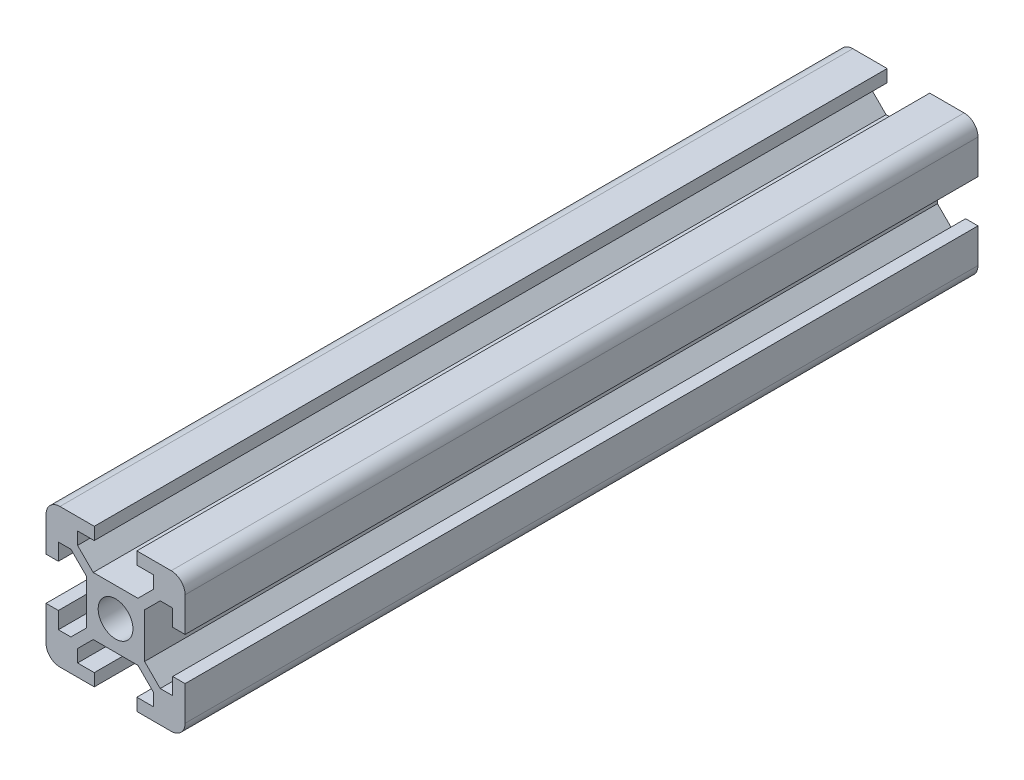
SolidWorks part; units mm, degrees
material "1060 Alloy"
ref_plane "Front Plane" through (0, 0, 0) normal (0, 0, 1) x (1, 0, 0)
ref_plane "Top Plane" through (0, 0, 0) normal (0, 1, 0) x (1, 0, 0)
ref_plane "Right Plane" through (0, 0, 0) normal (1, 0, 0) x (0, 0, -1)
sketch "Sketch1" plane through (0, 0, 0) normal (0, 0, 1) x (1, 0, 0)
  line L0 (-5.46, -6.42) -> (-3.215, -4.175)
  line L1 (-10, -10) -> (-3.06, -10)
  line L2 (-10, -10) -> (-10, -3.06)
  line L3 (-10, 10) -> (-3.06, 10)
  line L4 (10, -10) -> (10, -3.06)
  line L5 (-10, -10) -> (10, 10) construction
  line L6 (-10, 10) -> (10, -10) construction
  line L7 (-3.215, -4.175) -> (3.215, -4.175)
  line L8 (-4.175, -3.215) -> (-4.175, 3.215)
  line L9 (-3.215, 4.175) -> (3.215, 4.175)
  line L10 (4.175, -3.215) -> (4.175, 3.215)
  line L11 (-4.175, -4.175) -> (4.175, 4.175) construction
  line L12 (-4.175, 4.175) -> (4.175, -4.175) construction
  line L13 (-5.46, 6.42) -> (-5.46, 8.22)
  line L14 (-5.46, 8.22) -> (-3.06, 8.22)
  line L15 (-3.06, 8.22) -> (-3.06, 10)
  line L16 (-6.42, -5.46) -> (-4.175, -3.215)
  line L17 (5.46, 6.42) -> (5.46, 8.22)
  line L18 (5.46, 8.22) -> (3.06, 8.22)
  line L19 (3.06, 8.22) -> (3.06, 10)
  line L20 (-5.46, 6.42) -> (-3.215, 4.175)
  line L21 (6.42, 5.46) -> (8.22, 5.46)
  line L22 (8.22, 5.46) -> (8.22, 3.06)
  line L23 (8.22, 3.06) -> (10, 3.06)
  line L24 (8.22, -5.46) -> (6.42, -5.46)
  line L25 (-6.42, 5.46) -> (-4.175, 3.215)
  line L26 (8.22, -5.46) -> (8.22, -3.06)
  line L27 (8.22, -3.06) -> (10, -3.06)
  line L28 (5.46, 6.42) -> (3.215, 4.175)
  line L29 (5.46, -6.42) -> (5.46, -8.22)
  line L30 (5.46, -8.22) -> (3.06, -8.22)
  line L31 (3.06, -8.22) -> (3.06, -10)
  line L32 (6.42, 5.46) -> (4.175, 3.215)
  line L33 (-6.42, 5.46) -> (-8.22, 5.46)
  line L34 (-8.22, 5.46) -> (-8.22, 3.06)
  line L35 (-8.22, 3.06) -> (-10, 3.06)
  line L36 (6.42, -5.46) -> (4.175, -3.215)
  line L37 (-6.42, -5.46) -> (-8.22, -5.46)
  line L38 (-8.22, -5.46) -> (-8.22, -3.06)
  line L39 (-8.22, -3.06) -> (-10, -3.06)
  line L40 (5.46, -6.42) -> (3.215, -4.175)
  line L41 (-5.46, -6.42) -> (-5.46, -8.22)
  line L42 (-5.46, -8.22) -> (-3.06, -8.22)
  line L43 (-3.06, -8.22) -> (-3.06, -10)
  line L44 (-10, 3.06) -> (-10, 10)
  line L45 (3.06, 10) -> (10, 10)
  line L46 (10, 3.06) -> (10, 10)
  line L47 (3.06, -10) -> (10, -10)
  circle A0 centre (0, 0) radius 2.5
  point P0 (0, 0)
  dimension "D3" = 5
  dimension "D1" = 20
  dimension "D2" = 20
  dimension "D4" = 8.35
  dimension "D5" = 8.35
  dimension "D6" = 6.94
  dimension "D7" = 1.78
  dimension "D8" = 2.4
  dimension "D9" = 1.8
extrude "Boss-Extrude1" add sketch "Sketch1" along normal blind 114
fillet "Fillet1" radius 2 4 edges at (-10, -10, 57) (10, -10, 57) (-10, 10, 57) (10, 10, 57)
ref_plane "Plane1" through (0, 0, -156) normal (0, 0, 1) x (1, 0, 0)
ref_plane "Plane2" through (0, 0, 0) normal (1, 0, 0) x (0, 0, -1)
ref_plane "Plane3" through (0, 0, 0) normal (0, 1, 0) x (1, 0, 0)
